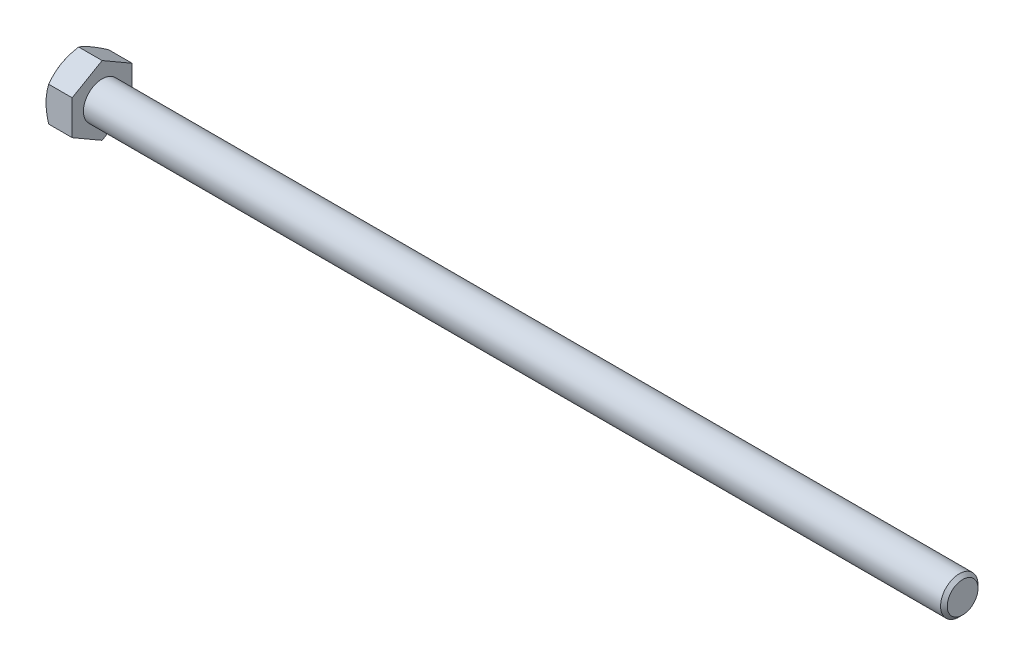
SolidWorks part; units mm, degrees
ref_plane "Plane1" through (0, 0, 0) normal (0, 0, 1) x (1, 0, 0)
ref_plane "Plane2" through (0, 0, 0) normal (0, 1, 0) x (1, 0, 0)
ref_plane "Plane3" through (0, 0, 0) normal (1, 0, 0) x (0, 0, -1)
sketch "Sketch1" plane through (0, 0, 0) normal (1, 0, 0) x (0, 0, -1)
  line L0 (4, 2.3094) -> (4, -2.3094)
  line L1 (-4, 2.3094) -> (-4, -2.3094)
  line L2 (4, -2.3094) -> (0, -4.6188)
  line L3 (0, -4.6188) -> (-4, -2.3094)
  line L4 (4, 2.3094) -> (0, 4.6188)
  line L5 (0, 4.6188) -> (-4, 2.3094)
  dimension "Width_flats" = 8
  dimension "D2" = 120
  dimension "D3" = 4
  dimension "D4" = 4
  dimension "D5" = 4
extrude "BaseHead" add sketch "Sketch1" along normal blind 3.5
sketch "BodySke" plane through (0, 0, 0) normal (0, 0, 1) x (1, 0, 0)
  line L1 (0, 0) -> (118.5, 0)
  line L2 (0, 0) -> (0, 2.5)
  line L4 (118.5, 0) -> (118.5, 2.055)
  line L5 (3.5, 4.6188) -> (3.5, 2.3094) construction
  line L6 (118.5, 2.055) -> (118.055, 2.5)
  line L7 (0, 0) -> (110.49, 0) construction
  line L8 (118.5, -2.055) -> (118.055, -2.5) construction
  line L9 (0, 2.3094) -> (0, -2.3094) construction
  line L10 (4.3, 15.24) -> (4.3, -1.27) construction
  line L11 (102.5, 15.24) -> (102.5, -1.27) construction
  line L12 (3.5, 2.3094) -> (3.5, -2.3094) construction
  line L15 (0, 2.5) -> (118.055, 2.5)
  dimension "Length" = 115
  dimension "Body_ch_ang" = 45
  dimension "Diameter" = 5
  dimension "Minor_dia" = 4.11
  dimension "Advance" = 0.8
  dimension "Thread_nom" = 16
revolve "BaseBody" add sketch "BodySke" angle 360 about L7
cosmetic thread "Représentation de filetage1" parameters "D1"=16, "D2"=4.11
sketch "Sketch3" plane through (0, 0, 0) normal (0, 0, 1) x (1, 0, 0)
  line L0 (0, 4) -> (3.244, 9.6188)
  line L1 (0, 4.6188) -> (0, 2.3094) construction
  line L2 (3.244, 9.6188) -> (3.244, 14.6188)
  line L3 (3.244, 14.6188) -> (-10, 14.6188)
  line L4 (-10, 14.6188) -> (-10, 4)
  line L5 (-10, 4) -> (0, 4)
  line L6 (0, 0) -> (99.06, 0) construction
  line L7 (3.5, 4.6188) -> (0, 4.6188) construction
  dimension "D1" = 4
  dimension "D2" = 5
  dimension "D3" = 10
  dimension "D4" = 5
  dimension "Head_ch_ang" = 30
revolve "HeadChamfer" cut sketch "Sketch3" angle 360 about L6
